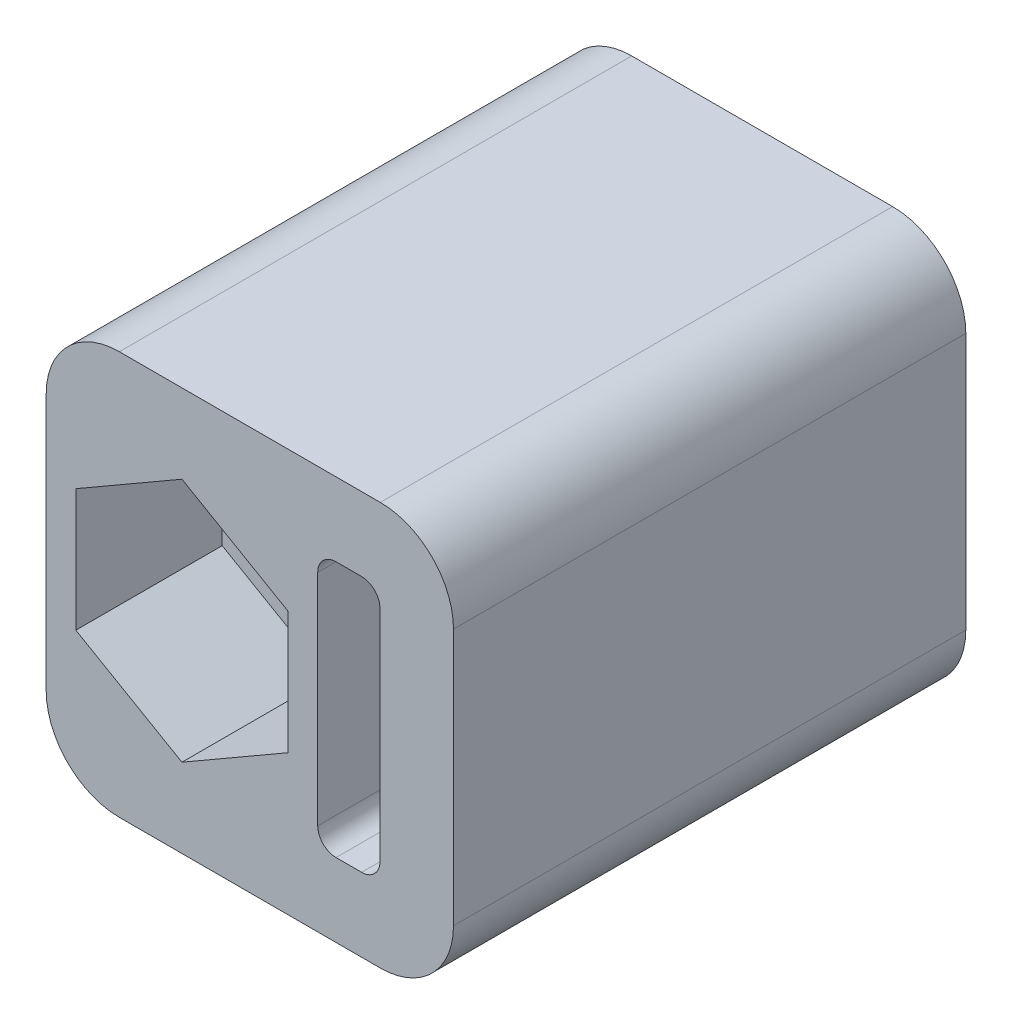
SolidWorks part; units mm, degrees
ref_plane "Front Plane" through (0, 0, 0) normal (0, 0, 1) x (1, 0, 0)
ref_plane "Top Plane" through (0, 0, 0) normal (0, 1, 0) x (1, 0, 0)
ref_plane "Right Plane" through (0, 0, 0) normal (1, 0, 0) x (0, 0, -1)
sketch "Sketch1" plane through (0, 0, 0) normal (0, 0, 1) x (1, 0, 0)
  line L4 (5.42, 5.51) -> (-1.71, 5.51)
  line L5 (7.42, 3.51) -> (7.42, -3.51)
  line L6 (5.42, -5.51) -> (-1.71, -5.51)
  line L7 (-3.71, 3.51) -> (-3.71, -3.51)
  line L18 (4.21, 3.5) -> (4.91, 3.5)
  line L19 (3.71, 3) -> (3.71, -3)
  line L20 (4.21, -3.5) -> (4.91, -3.5)
  line L21 (5.41, 3) -> (5.41, -3)
  circle A4 centre (0, 0) radius 1.7
  arc A5 (-1.71, -5.51) -> (-3.71, -3.51) centre (-1.71, -3.51) cw
  arc A6 (-1.71, 5.51) -> (-3.71, 3.51) centre (-1.71, 3.51) ccw
  arc A7 (5.42, 5.51) -> (7.42, 3.51) centre (5.42, 3.51) cw
  arc A8 (7.42, -3.51) -> (5.42, -5.51) centre (5.42, -3.51) cw
  arc A10 (5.41, -3) -> (4.91, -3.5) centre (4.91, -3) cw
  arc A11 (3.71, -3) -> (4.21, -3.5) centre (4.21, -3) ccw
  arc A12 (4.91, 3.5) -> (5.41, 3) centre (4.91, 3) cw
  arc A13 (3.71, 3) -> (4.21, 3.5) centre (4.21, 3) cw
extrude "Boss-Extrude1" add sketch "Sketch1" along normal blind 14
sketch "Sketch2" plane through (0, 0, 14) normal (0, 0, 1) x (1, 0, 0)
  line L0 (0, 3.3486) -> (-2.9, 1.6743)
  line L1 (-2.9, 1.6743) -> (-2.9, -1.6743)
  line L2 (-2.9, -1.6743) -> (0, -3.3486)
  line L3 (0, -3.3486) -> (2.9, -1.6743)
  line L4 (2.9, -1.6743) -> (2.9, 1.6743)
  line L5 (2.9, 1.6743) -> (0, 3.3486)
extrude "Cut-Extrude1" cut sketch "Sketch2" against normal blind 4
